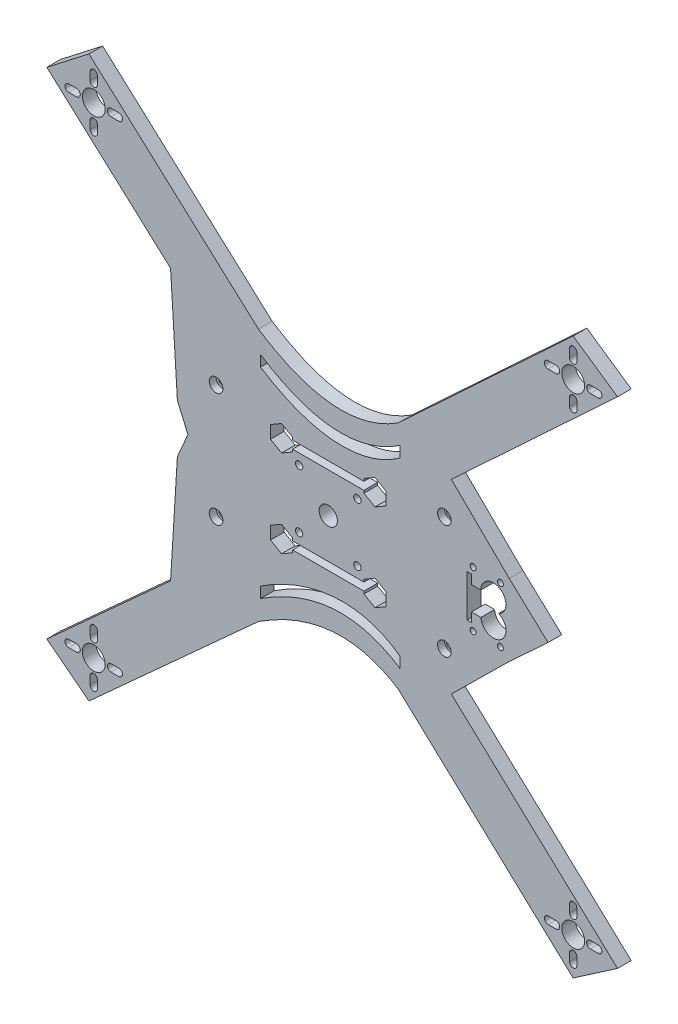
SolidWorks part; units mm, degrees
ref_plane "Front Plane" through (0, 0, 0) normal (0, 0, 1) x (1, 0, 0)
ref_plane "Top Plane" through (0, 0, 0) normal (0, 1, 0) x (1, 0, 0)
ref_plane "Right Plane" through (0, 0, 0) normal (1, 0, 0) x (0, 0, -1)
sketch "Sketch2" plane through (0, 0, 0) normal (0, 0, 1) x (1, 0, 0)
  line L13 (60.0519, 43.683) -> (126.6953, 108.4225) construction
  line L14 (107.2681, 121.7638) -> (30.6437, 50.4926)
  line L17 (-30.5776, 55.4657) -> (-104.8153, 122.7377)
  line L18 (-123.2702, 108.4225) -> (-69.068, 59.3061)
  line L21 (-78.2335, 0) -> (58.2955, 0) construction
  line L25 (53.914, 40.7259) -> (126.6953, 108.4225)
  line L26 (-69.068, 59.3061) -> (-66.0791, 10.6231)
  line L27 (-66.0791, 10.6231) -> (-61.4571, 0)
  line L30 (31.4696, 42.3446) -> (31.4696, 37.5942)
  line L31 (-29.6757, 46.3017) -> (-29.6757, 41.5513)
  line L32 (50.8711, 25) -> (-49.128, 25) construction
  line L75 (46.9445, 95.5866) -> (6.6629, 95.5866) construction
  line L84 (118.2959, 105.3359) -> (114.7959, 105.3359) construction
  line L102 (91.6078, 89.3609) -> (-155.0881, 89.3609) construction
  line L104 (-91.7041, 105.3359) -> (-95.2041, 105.3359) construction
  line L105 (-91.7041, 103.7359) -> (-95.2041, 103.7359)
  line L106 (-91.7041, 106.9359) -> (-95.2041, 106.9359)
  line L107 (-102.7041, 94.3359) -> (-102.7041, 97.8359) construction
  line L108 (-104.3041, 94.3359) -> (-104.3041, 97.8359)
  line L109 (-101.1041, 94.3359) -> (-101.1041, 97.8359)
  line L110 (-113.7041, 105.3359) -> (-110.2041, 105.3359) construction
  line L111 (-113.7041, 106.9359) -> (-110.2041, 106.9359)
  line L112 (-113.7041, 103.7359) -> (-110.2041, 103.7359)
  line L113 (-102.7041, 116.3359) -> (-102.7041, 112.8359) construction
  line L114 (-101.1041, 116.3359) -> (-101.1041, 112.8359)
  line L115 (-104.3041, 116.3359) -> (-104.3041, 112.8359)
  line L157 (-102.7041, -104.6641) -> (-102.7041, 105.3359) construction
  line L158 (-102.7041, 105.3359) -> (107.2959, 105.3359) construction
  line L159 (107.2959, -104.6641) -> (107.2959, 105.3359) construction
  line L160 (118.2959, 103.7359) -> (114.7959, 103.7359)
  line L162 (118.2959, 106.9359) -> (114.7959, 106.9359)
  line L163 (107.2959, 94.3359) -> (107.2959, 97.8359) construction
  line L164 (105.6959, 94.3359) -> (105.6959, 97.8359)
  line L165 (108.8959, 94.3359) -> (108.8959, 97.8359)
  line L166 (96.2959, 105.3359) -> (99.7959, 105.3359) construction
  line L167 (96.2959, 106.9359) -> (99.7959, 106.9359)
  line L168 (96.2959, 103.7359) -> (99.7959, 103.7359)
  line L169 (107.2959, 116.3359) -> (107.2959, 112.8359) construction
  line L170 (108.8959, 116.3359) -> (108.8959, 112.8359)
  line L171 (105.6959, 116.3359) -> (105.6959, 112.8359)
  line L172 (107.2681, 121.7638) -> (126.6953, 108.4225)
  line L173 (-104.8153, 122.7377) -> (-123.2702, 108.4225)
  line L174 (118.2959, -105.3359) -> (114.7959, -105.3359) construction
  line L175 (118.2959, -103.7359) -> (114.7959, -103.7359)
  line L176 (118.2959, -106.9359) -> (114.7959, -106.9359)
  line L177 (-91.7041, -105.3359) -> (-95.2041, -105.3359) construction
  line L178 (-91.7041, -103.7359) -> (-95.2041, -103.7359)
  line L179 (-91.7041, -106.9359) -> (-95.2041, -106.9359)
  line L180 (-102.7041, -94.3359) -> (-102.7041, -97.8359) construction
  line L181 (-104.3041, -94.3359) -> (-104.3041, -97.8359)
  line L182 (-101.1041, -94.3359) -> (-101.1041, -97.8359)
  line L183 (-113.7041, -105.3359) -> (-110.2041, -105.3359) construction
  line L184 (-113.7041, -106.9359) -> (-110.2041, -106.9359)
  line L185 (-113.7041, -103.7359) -> (-110.2041, -103.7359)
  line L186 (-102.7041, -116.3359) -> (-102.7041, -112.8359) construction
  line L187 (-101.1041, -116.3359) -> (-101.1041, -112.8359)
  line L188 (-104.3041, -116.3359) -> (-104.3041, -112.8359)
  line L189 (107.2959, -94.3359) -> (107.2959, -97.8359) construction
  line L190 (105.6959, -94.3359) -> (105.6959, -97.8359)
  line L191 (108.8959, -94.3359) -> (108.8959, -97.8359)
  line L192 (96.2959, -105.3359) -> (99.7959, -105.3359) construction
  line L193 (96.2959, -106.9359) -> (99.7959, -106.9359)
  line L194 (96.2959, -103.7359) -> (99.7959, -103.7359)
  line L195 (107.2959, -116.3359) -> (107.2959, -112.8359) construction
  line L196 (108.8959, -116.3359) -> (108.8959, -112.8359)
  line L197 (105.6959, -116.3359) -> (105.6959, -112.8359)
  line L198 (-102.7041, -105.3359) -> (107.2959, -105.3359) construction
  line L199 (91.6078, -89.3609) -> (-155.0881, -89.3609) construction
  line L200 (46.9445, -95.5866) -> (6.6629, -95.5866) construction
  line L201 (50.8711, -25) -> (-49.128, -25) construction
  line L202 (60.0519, -43.683) -> (126.6953, -108.4225) construction
  line L203 (-104.8153, -122.7377) -> (-123.2702, -108.4225)
  line L204 (107.2681, -121.7638) -> (126.6953, -108.4225)
  line L206 (-29.6757, -46.3017) -> (-29.6757, -41.5513)
  line L207 (31.4696, -42.3446) -> (31.4696, -37.5942)
  line L208 (-66.0791, -10.6231) -> (-61.4571, 0)
  line L209 (-69.068, -59.3061) -> (-66.0791, -10.6231)
  line L210 (53.914, -40.7259) -> (126.6953, -108.4225)
  line L211 (-123.2702, -108.4225) -> (-69.068, -59.3061)
  line L212 (-30.5776, -55.4657) -> (-104.8153, -122.7377)
  line L213 (107.2681, -121.7638) -> (30.6437, -50.4926)
  line L218 (62.7188, 9.1831) -> (60.819, 9.1831)
  line L219 (62.7188, 9.1831) -> (62.7188, 5.1871)
  line L221 (60.819, 9.1831) -> (60.819, 5.1871)
  line L222 (60.819, -9.1831) -> (60.819, -5.1871)
  line L224 (62.7188, -9.1831) -> (62.7188, -5.1871)
  line L225 (62.7188, -9.1831) -> (60.819, -9.1831)
  line L226 (62.7188, -5.1871) -> (66.8596, -5.1871)
  line L228 (60.819, 5.1871) -> (60.819, -5.1871)
  line L233 (62.7188, 5.1871) -> (66.8457, 5.1871)
  line L238 (53.914, 40.7259) -> (79.2751, 15.802)
  line L239 (96.2959, 0) -> (79.2751, 15.802)
  line L240 (96.2959, 0) -> (79.2751, -15.698)
  line L241 (53.914, -40.7259) -> (79.2751, -15.698)
  circle A1 centre (50.8711, 25) radius 2.1288
  circle A3 centre (-49.128, 25) radius 1.8864
  circle A67 centre (-102.7041, 105.3359) radius 5
  arc A98 (-91.7041, 103.7359) -> (-91.7041, 106.9359) centre (-91.7041, 105.3359) ccw
  arc A99 (-95.2041, 106.9359) -> (-95.2041, 103.7359) centre (-95.2041, 105.3359) ccw
  arc A100 (-104.3041, 94.3359) -> (-101.1041, 94.3359) centre (-102.7041, 94.3359) ccw
  arc A101 (-101.1041, 97.8359) -> (-104.3041, 97.8359) centre (-102.7041, 97.8359) ccw
  arc A102 (-113.7041, 106.9359) -> (-113.7041, 103.7359) centre (-113.7041, 105.3359) ccw
  arc A103 (-110.2041, 103.7359) -> (-110.2041, 106.9359) centre (-110.2041, 105.3359) ccw
  arc A104 (-101.1041, 116.3359) -> (-104.3041, 116.3359) centre (-102.7041, 116.3359) ccw
  arc A105 (-104.3041, 112.8359) -> (-101.1041, 112.8359) centre (-102.7041, 112.8359) ccw
  circle A128 centre (107.2959, 105.3359) radius 5
  arc A129 (118.2959, 103.7359) -> (118.2959, 106.9359) centre (118.2959, 105.3359) ccw
  arc A130 (114.7959, 106.9359) -> (114.7959, 103.7359) centre (114.7959, 105.3359) ccw
  arc A131 (105.6959, 94.3359) -> (108.8959, 94.3359) centre (107.2959, 94.3359) ccw
  arc A132 (108.8959, 97.8359) -> (105.6959, 97.8359) centre (107.2959, 97.8359) ccw
  arc A133 (96.2959, 106.9359) -> (96.2959, 103.7359) centre (96.2959, 105.3359) ccw
  arc A134 (99.7959, 103.7359) -> (99.7959, 106.9359) centre (99.7959, 105.3359) ccw
  arc A135 (108.8959, 116.3359) -> (105.6959, 116.3359) centre (107.2959, 116.3359) ccw
  arc A136 (105.6959, 112.8359) -> (108.8959, 112.8359) centre (107.2959, 112.8359) ccw
  arc A137 (118.2959, -103.7359) -> (118.2959, -106.9359) centre (118.2959, -105.3359) cw
  arc A138 (114.7959, -106.9359) -> (114.7959, -103.7359) centre (114.7959, -105.3359) cw
  arc A139 (-91.7041, -103.7359) -> (-91.7041, -106.9359) centre (-91.7041, -105.3359) cw
  arc A140 (-95.2041, -106.9359) -> (-95.2041, -103.7359) centre (-95.2041, -105.3359) cw
  arc A141 (-104.3041, -94.3359) -> (-101.1041, -94.3359) centre (-102.7041, -94.3359) cw
  arc A142 (-101.1041, -97.8359) -> (-104.3041, -97.8359) centre (-102.7041, -97.8359) cw
  arc A143 (-113.7041, -106.9359) -> (-113.7041, -103.7359) centre (-113.7041, -105.3359) cw
  arc A144 (-110.2041, -103.7359) -> (-110.2041, -106.9359) centre (-110.2041, -105.3359) cw
  arc A145 (-101.1041, -116.3359) -> (-104.3041, -116.3359) centre (-102.7041, -116.3359) cw
  arc A146 (-104.3041, -112.8359) -> (-101.1041, -112.8359) centre (-102.7041, -112.8359) cw
  arc A147 (105.6959, -94.3359) -> (108.8959, -94.3359) centre (107.2959, -94.3359) cw
  arc A148 (108.8959, -97.8359) -> (105.6959, -97.8359) centre (107.2959, -97.8359) cw
  arc A149 (96.2959, -106.9359) -> (96.2959, -103.7359) centre (96.2959, -105.3359) cw
  arc A150 (99.7959, -103.7359) -> (99.7959, -106.9359) centre (99.7959, -105.3359) cw
  arc A151 (108.8959, -116.3359) -> (105.6959, -116.3359) centre (107.2959, -116.3359) cw
  arc A152 (105.6959, -112.8359) -> (108.8959, -112.8359) centre (107.2959, -112.8359) cw
  circle A153 centre (107.2959, -105.3359) radius 5
  circle A154 centre (-102.7041, -105.3359) radius 5
  circle A155 centre (-49.128, -25) radius 1.8864
  circle A156 centre (50.8711, -25) radius 2.1288
  circle A157 centre (63.4344, 12.2109) radius 1.3
  circle A158 centre (75.4344, 12.202) radius 1.3
  circle A159 centre (63.4344, -12.098) radius 1.3
  circle A160 centre (75.4344, -12.098) radius 1.3
  arc A162 (74.6549, 0.1954) -> (66.8457, 5.1871) centre (72.3457, 5.1871) ccw
  arc A163 (66.8596, -5.1871) -> (74.6549, 0.1954) centre (72.3457, -4.7964) ccw
  spline S0 degree 2 poles (-30.5776, 55.4657) (3.6892, 33.1025) (30.6437, 50.4926) knots 0 0 0 1 1 1
  spline S1 degree 3 poles (-29.6757, -41.5513) (-7.0535, -26.7882) (14.9745, -25.6317) (31.4696, -37.5942) knots 0 0 0 0 1 1 1 1
  spline S2 degree 2 poles (-29.6757, 46.3017) (4.2576, 24.157) (31.4696, 42.3446) knots 0 0 0 1 1 1
  spline S3 degree 3 poles (-29.6757, 41.5513) (-7.0535, 26.7882) (14.9745, 25.6317) (31.4696, 37.5942) knots 0 0 0 0 1 1 1 1
  spline S4 degree 2 poles (-29.6757, -46.3017) (4.2576, -24.157) (31.4696, -42.3446) knots 0 0 0 1 1 1
  spline S5 degree 2 poles (-30.5776, -55.4657) (3.6892, -33.1025) (30.6437, -50.4926) knots 0 0 0 1 1 1
  point P11 (-93.4541, 105.3359)
  point P15 (116.5459, 105.3359)
  point P24 (107.2959, 96.0859)
  point P33 (98.0459, 105.3359)
  point P44 (107.2959, 114.5859)
  point P57 (107.2959, 105.3359)
  point P62 (116.5459, -105.3359)
  point P70 (-102.7041, 96.0859)
  point P79 (-111.9541, 105.3359)
  point P86 (-102.7041, 114.5859)
  point P93 (-102.7041, 105.3359)
  point P99 (-93.4541, -105.3359)
  point P106 (-102.7041, -96.0859)
  point P113 (-111.9541, -105.3359)
  point P120 (-102.7041, -114.5859)
  point P127 (107.2959, -96.0859)
  point P134 (98.0459, -105.3359)
  point P141 (107.2959, -114.5859)
  point P174 (-102.7041, -105.3359)
  point P175 (107.2959, -105.3359)
  point P181 (96.2959, 0.1954)
  dimension "D7" = 2.6
  dimension "D8" = 11
  dimension "D1" = 210
  dimension "D2" = 210
  dimension "D3" = 23
  dimension "D4" = 23
  dimension "D5" = 24.3
  dimension "D6" = 12
extrude "Boss-Extrude1" add sketch "Sketch2" along normal blind 6
sketch "Sketch4" plane through (0, 0, 6) normal (0, 0, 1) x (1, 0, 0)
  line L1 (-15.6174, 20.8229) -> (15.6174, 20.8229)
  line L3 (-15.6174, 17.4) -> (15.6174, 17.4)
  line L5 (0, 17.4) -> (0, 13.7218) construction
  line L6 (15.6174, 20.8229) -> (15.6174, 21.9099)
  line L7 (0, 23.2934) -> (0, 20.8229) construction
  line L8 (15.6174, 21.9099) -> (20.4644, 24.7083)
  line L9 (-20.4644, 24.7083) -> (-25.3114, 21.9099)
  line L10 (-25.3114, 21.9099) -> (-25.3114, 16.3131)
  line L11 (-25.3114, 16.3131) -> (-20.4644, 13.5147)
  line L12 (-20.4644, 13.5147) -> (-15.6174, 16.3131)
  line L13 (-15.6174, 16.3131) -> (-15.6174, 17.4)
  line L14 (-15.6174, 21.9099) -> (-20.4644, 24.7083)
  line L15 (15.6174, 16.3131) -> (15.6174, 17.4)
  line L16 (20.4644, 13.5147) -> (15.6174, 16.3131)
  line L17 (25.3114, 16.3131) -> (20.4644, 13.5147)
  line L18 (25.3114, 21.9099) -> (25.3114, 16.3131)
  line L19 (20.4644, 24.7083) -> (25.3114, 21.9099)
  line L20 (0, -23.2934) -> (0, -20.8229) construction
  line L21 (-15.6174, 20.8229) -> (-15.6174, 21.9099)
  line L22 (0, -17.4) -> (0, -13.7218) construction
  line L23 (-15.6174, -20.8229) -> (-15.6174, -21.9099)
  line L24 (20.4644, -24.7083) -> (25.3114, -21.9099)
  line L25 (25.3114, -21.9099) -> (25.3114, -16.3131)
  line L26 (25.3114, -16.3131) -> (20.4644, -13.5147)
  line L27 (20.4644, -13.5147) -> (15.6174, -16.3131)
  line L28 (15.6174, -16.3131) -> (15.6174, -17.4)
  line L29 (-15.6174, -21.9099) -> (-20.4644, -24.7083)
  line L30 (-15.6174, -16.3131) -> (-15.6174, -17.4)
  line L31 (-20.4644, -13.5147) -> (-15.6174, -16.3131)
  line L32 (-25.3114, -16.3131) -> (-20.4644, -13.5147)
  line L33 (-25.3114, -21.9099) -> (-25.3114, -16.3131)
  line L34 (-20.4644, -24.7083) -> (-25.3114, -21.9099)
  line L35 (15.6174, -21.9099) -> (20.4644, -24.7083)
  line L36 (15.6174, -20.8229) -> (15.6174, -21.9099)
  line L37 (-15.6174, -17.4) -> (15.6174, -17.4)
  line L38 (-15.6174, -20.8229) -> (15.6174, -20.8229)
  circle A28 centre (0, 0) radius 4
  point P0 (0, 19.1115)
  point P44 (0, -19.1115)
  point P70 (69.6065, 12.2614)
  point P84 (55.1176, 16.1437)
  point P103 (40.6287, 20.026)
  point P250 (69.6065, 12.2614)
  point P257 (55.1176, 16.1437)
  point P264 (40.6287, 20.026)
  point P271 (69.6065, 12.2614)
  point P278 (55.1176, 16.1437)
  point P285 (40.6287, 20.026)
  point P292 (69.6065, 12.2614)
  point P299 (55.1176, 16.1437)
  point P306 (40.6287, 20.026)
  point P313 (69.6065, 12.2614)
  point P320 (55.1176, 16.1437)
  point P327 (40.6287, 20.026)
  point P334 (69.6065, 12.2614)
  point P341 (55.1176, 16.1437)
  point P348 (40.6287, 20.026)
  point P355 (69.6065, 12.2614)
  point P362 (55.1176, 16.1437)
  point P369 (40.6287, 20.026)
  point P376 (69.6065, 12.2614)
  point P383 (55.1176, 16.1437)
  point P390 (40.6287, 20.026)
  point P397 (69.6065, 12.2614)
  point P404 (55.1176, 16.1437)
  point P411 (40.6287, 20.026)
  point P418 (69.6065, 12.2614)
  point P425 (55.1176, 16.1437)
  point P432 (40.6287, 20.026)
  point P439 (69.6065, 12.2614)
  point P446 (55.1176, 16.1437)
  point P453 (40.6287, 20.026)
  point P460 (69.6065, 12.2614)
  point P467 (55.1176, 16.1437)
  point P474 (40.6287, 20.026)
  point P481 (69.6065, 12.2614)
  point P488 (55.1176, 16.1437)
  point P495 (40.6287, 20.026)
  dimension "D4" = 8
extrude "Cut-Extrude1" cut sketch "Sketch4" against normal through all
sketch "Sketch6" plane through (0, 0, 0) normal (0, 0, -1) x (-1, 0, 0)
  line L1 (-12.75, -12.75) -> (12.75, -12.75) construction
  line L2 (-12.75, -12.75) -> (-12.75, 12.75) construction
  line L3 (-12.75, 12.75) -> (12.75, 12.75) construction
  line L4 (12.75, -12.75) -> (12.75, 12.75) construction
  line L5 (-12.75, -12.75) -> (12.75, 12.75) construction
  line L6 (-12.75, 12.75) -> (12.75, -12.75) construction
  circle A0 centre (-12.75, 12.75) radius 1.6
  circle A1 centre (12.75, 12.75) radius 1.6
  circle A2 centre (12.75, -12.75) radius 1.6
  circle A3 centre (-12.75, -12.75) radius 1.6
  point P0 (0, 0)
  dimension "D3" = 3.2
  dimension "D1" = 25.5
  dimension "D2" = 25.5
extrude "Cut-Extrude2" cut sketch "Sketch6" against normal blind 10
sketch "Sketch7" plane through (0, 0, 6) normal (0, 0, 1) x (1, 0, 0)
  circle A0 centre (-49.128, 25) radius 3
  circle A1 centre (-49.128, -25) radius 3
  circle A2 centre (50.8711, -25) radius 3
  circle A3 centre (50.8711, 25) radius 3
  dimension "D1" = 6
extrude "Cut-Extrude3" cut sketch "Sketch7" against normal blind 3
